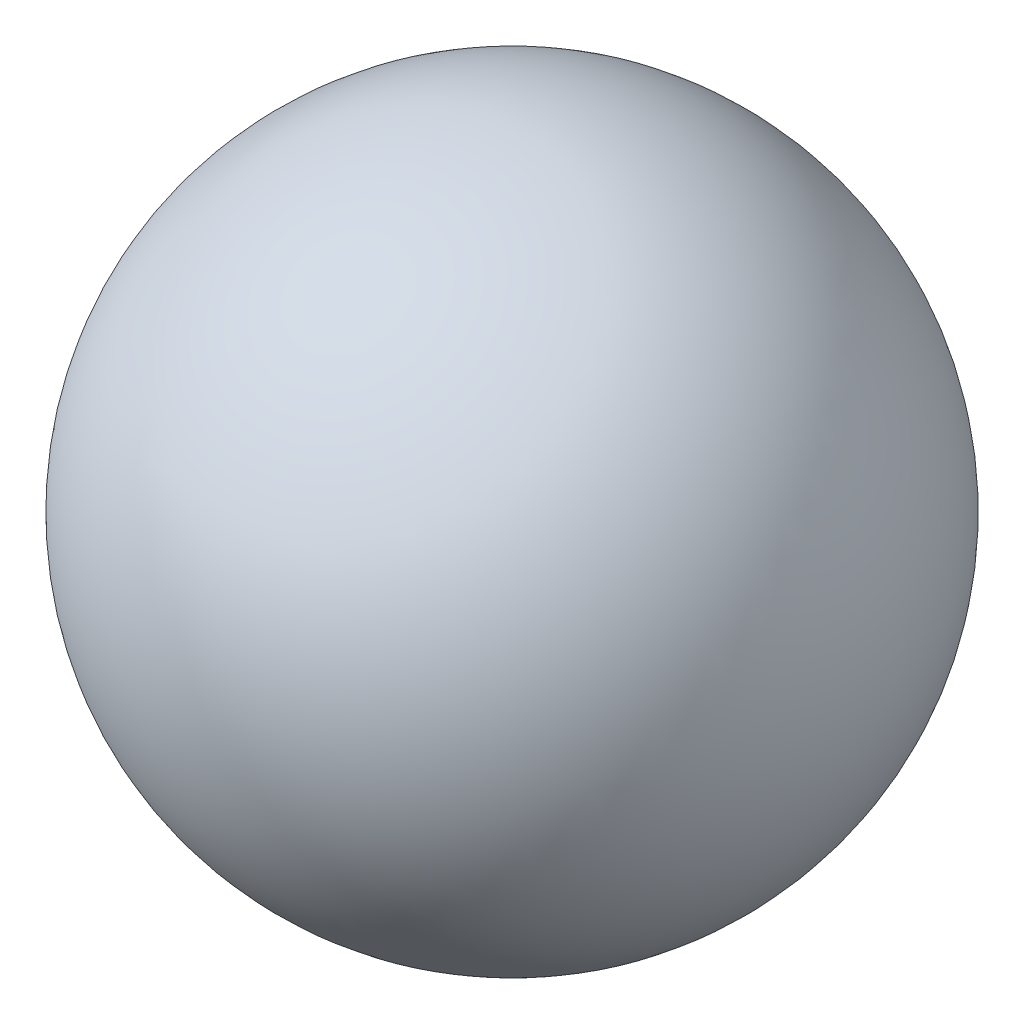
SolidWorks part; units mm, degrees
ref_plane "Ön Düzlem" through (0, 0, 0) normal (0, 0, 1) x (1, 0, 0)
ref_plane "Üst Düzlem" through (0, 0, 0) normal (0, 1, 0) x (1, 0, 0)
ref_plane "Sağ Düzlem" through (0, 0, 0) normal (1, 0, 0) x (0, 0, -1)
sketch "Sketch1" plane through (0, 0, 0) normal (0, 0, 1) x (1, 0, 0)
  line L0 (0, 28.56) -> (0, -28.56)
  arc A0 (0, 28.56) -> (0, -28.56) centre (0, 0) ccw
  dimension "D1" = 57.12
revolve "Revolve5" add sketch "Sketch1" angle 360 about L0
